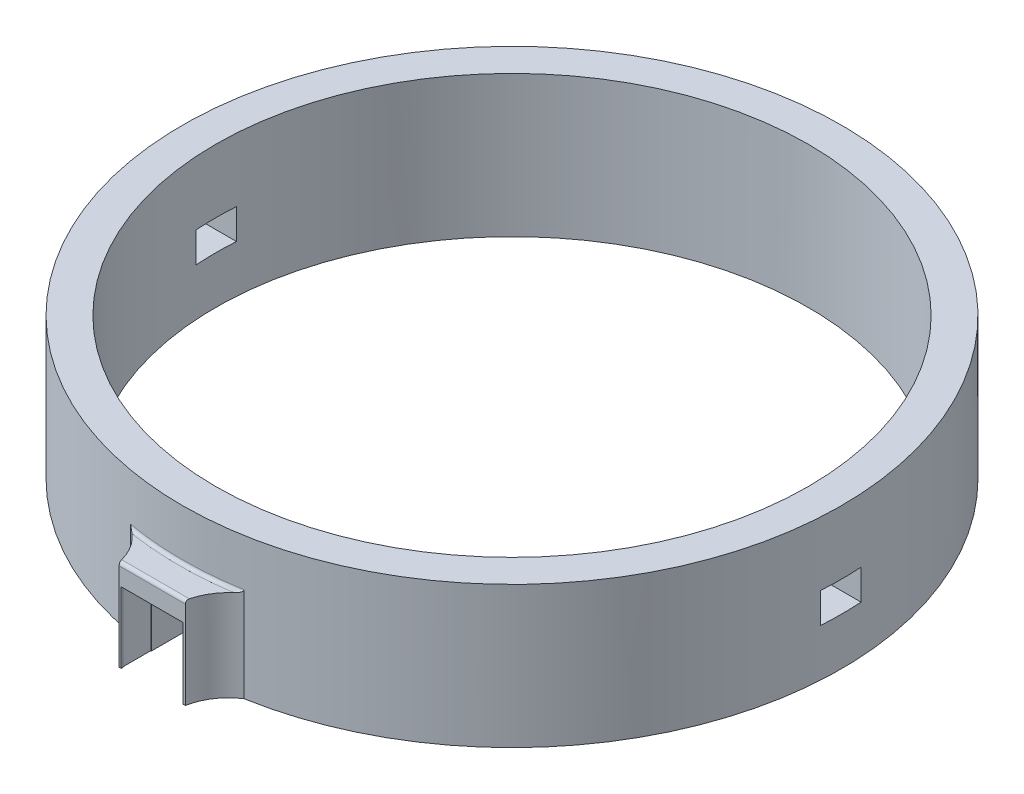
SolidWorks part; units mm, degrees
ref_plane "Front Plane" through (0, 0, 0) normal (0, 0, 1) x (1, 0, 0)
ref_plane "Top Plane" through (0, 0, 0) normal (0, 1, 0) x (1, 0, 0)
ref_plane "Right Plane" through (0, 0, 0) normal (1, 0, 0) x (0, 0, -1)
sketch "Sketch1" plane through (0, 0, 0) normal (0, 1, 0) x (1, 0, 0)
  circle A0 centre (0, 0) radius 9945.7494
  circle A1 centre (0, 0) radius 9500
  dimension "D1" = 19891.4989
  dimension "D2" = 19000
extrude "Boss-Extrude1" add sketch "Sketch1" along normal blind 4267.2 contours A0
sketch "Sketch2" plane through (0, 4267.2, 0) normal (0, 1, 0) x (1, 0, 0)
  circle A0 centre (0, 0) radius 8945.7494
  circle A1 centre (0, 0) radius 9945.7494 construction
  dimension "D1" = 1000
extrude "Cut-Extrude1" cut sketch "Sketch2" against normal blind 4267.2 contours A0
ref_plane "Plane2" through (0, 0, 9945.7494) normal (0, 0, 1) x (1, 0, 0)
sketch "Sketch4" plane through (0, 0, 9945.7494) normal (0, 0, 1) x (1, 0, 0)
  line L0 (0, -2346.96) -> (0, 2346.96) construction
  line L1 (1000, 0) -> (-1000, 0)
  line L2 (1000, 0) -> (1000, 2750)
  line L3 (1000, 2750) -> (-1000, 2750)
  line L4 (-1000, 0) -> (-1000, 2750)
  line L5 (1000, 0) -> (-1000, 2750) construction
  line L6 (1000, 2750) -> (-1000, 0) construction
  line L7 (10940.3244, 0) -> (-10940.3244, 0) construction
  point P0 (0, 1375)
  dimension "D1" = 2750
  dimension "D2" = 2000
extrude "Boss-Extrude2" add sketch "Sketch4" along normal blind 914.4 separate body
sketch "Sketch5" plane through (0, 0, 10860.1494) normal (0, 0, 1) x (1, 0, 0)
  line L0 (0, -2346.96) -> (0, 2346.96) construction
  line L1 (935, 0) -> (-935, 0)
  line L2 (935, 0) -> (935, 2135)
  line L3 (935, 2135) -> (-935, 2135)
  line L4 (-935, 0) -> (-935, 2135)
  line L5 (935, 0) -> (-935, 2135) construction
  line L6 (935, 2135) -> (-935, 0) construction
  line L7 (-1000, 0) -> (1000, 0) construction
  point P0 (0, 1067.5)
  dimension "D1" = 1870
  dimension "D2" = 2135
extrude "Cut-Extrude2" cut sketch "Sketch5" against normal mid plane 5000
sketch "Sketch6" plane through (-935, 0, 0) normal (1, 0, 0) x (0, 0, -1)
  line L0 (-10860.1494, 2135) -> (-10860.1494, 0) construction
  line L1 (-9945.7494, -75.4869) -> (-10810.1494, -75.4869)
  line L2 (-9945.7494, -75.4869) -> (-9945.7494, 2147.3115)
  line L3 (-9945.7494, 2147.3115) -> (-10810.1494, 2147.3115)
  line L4 (-10810.1494, -75.4869) -> (-10810.1494, 2147.3115)
  line L5 (-9945.7494, -75.4869) -> (-10810.1494, 2147.3115) construction
  line L6 (-9945.7494, 2147.3115) -> (-10810.1494, -75.4869) construction
  line L7 (-9945.7494, 2346.96) -> (-9945.7494, -2346.96) construction
  point P0 (-10377.9494, 1035.9123)
  dimension "D1" = 50
extrude "Cut-Extrude3" cut sketch "Sketch6" against normal blind 16.77
mirror "Mirror1" about plane through (0, 0, 0) normal (1, 0, 0) of "Cut-Extrude3"
sketch "Sketch7" plane through (0, 2135, 0) normal (0, -1, 0) x (1, 0, 0)
  line L0 (0, -2346.96) -> (0, 2346.96) construction
  line L1 (943.385, 10041.4502) -> (-943.385, 10041.4502)
  line L2 (943.385, 10041.4502) -> (943.385, 10810.1494)
  line L3 (943.385, 10810.1494) -> (-943.385, 10810.1494)
  line L4 (-943.385, 10041.4502) -> (-943.385, 10810.1494)
  line L5 (943.385, 10041.4502) -> (-943.385, 10810.1494) construction
  line L6 (943.385, 10810.1494) -> (-943.385, 10041.4502) construction
  line L7 (-951.77, 10810.1494) -> (-935, 10810.1494) construction
  line L8 (935, 10860.1494) -> (-935, 10860.1494) construction
  point P0 (0, 10425.7998)
  dimension "D1" = 50
extrude "Cut-Extrude4" cut sketch "Sketch7" against normal blind 16.77
sketch "Sketch8" plane through (0, 0, 0) normal (0, 1, 0) x (1, 0, 0)
  line L1 (-2346.96, -9945.7494) -> (2346.96, -9945.7494) construction
  line L2 (-1000, -10860.1494) -> (-1000, -9945.7494) construction
  line L3 (-1000, -9945.7494) -> (-1000, -10860.1494)
  line L4 (0, -2346.96) -> (0, 2346.96) construction
  line L5 (1000, -9945.7494) -> (1000, -10860.1494)
  line L6 (-1000, -9895.349) -> (1000, -9895.349)
  line L7 (1000, -9945.7494) -> (-1000, -9945.7494)
  circle A0 centre (0, 0) radius 9945.7494 construction
  arc A1 (-1000, -10860.1494) -> (-1709.7578, -9797.6865) centre (-2617.2235, -11172.2028) ccw
  arc A2 (-1709.7578, -9797.6865) -> (-1000, -9895.349) centre (0, 0) ccw
  arc A3 (1000, -10860.1494) -> (1709.7578, -9797.6865) centre (2617.2235, -11172.2028) cw
  arc A4 (1709.7578, -9797.6865) -> (1000, -9895.349) centre (0, 0) cw
extrude "Boss-Extrude3" add sketch "Sketch8" along normal up to surface (2750 mm away) up to face at (0, 2750, 10402.9494)
sketch "Sketch9" plane through (0, 0, 9945.7494) normal (0, 0, 1) x (1, 0, 0)
  line L1 (926.615, -141.7417) -> (-935, -141.7417)
  line L2 (926.615, -141.7417) -> (926.615, 2135)
  line L3 (926.615, 2135) -> (-935, 2135)
  line L4 (-935, -141.7417) -> (-935, 2135)
  line L5 (926.615, -141.7417) -> (-935, 2135) construction
  line L6 (926.615, 2135) -> (-935, -141.7417) construction
  point P0 (-4.1925, 996.6291)
extrude "Cut-Extrude5" cut sketch "Sketch9" against normal blind 4000
sketch "Sketch10" plane through (0, 0, 0) normal (1, 0, 0) x (0, 0, -1)
  line L0 (0, 2424.9179) -> (0, -2424.9179) construction
  line L1 (609.6, 1430.1679) -> (-609.6, 1430.1679)
  line L2 (609.6, 1430.1679) -> (609.6, 2344.5679)
  line L3 (609.6, 2344.5679) -> (-609.6, 2344.5679)
  line L4 (-609.6, 1430.1679) -> (-609.6, 2344.5679)
  line L5 (609.6, 1430.1679) -> (-609.6, 2344.5679) construction
  line L6 (609.6, 2344.5679) -> (-609.6, 1430.1679) construction
  point P0 (0, 1887.3679)
  dimension "D1" = 914.4
  dimension "D2" = 90
  dimension "D3" = 1219.2
extrude "Cut-Extrude6" cut sketch "Sketch10" against normal through all both and the other way through all
fillet "Fillet1" radius 100 2 edges at (0, 2750, 10860.1494) (0, 2750, 9945.7494)
